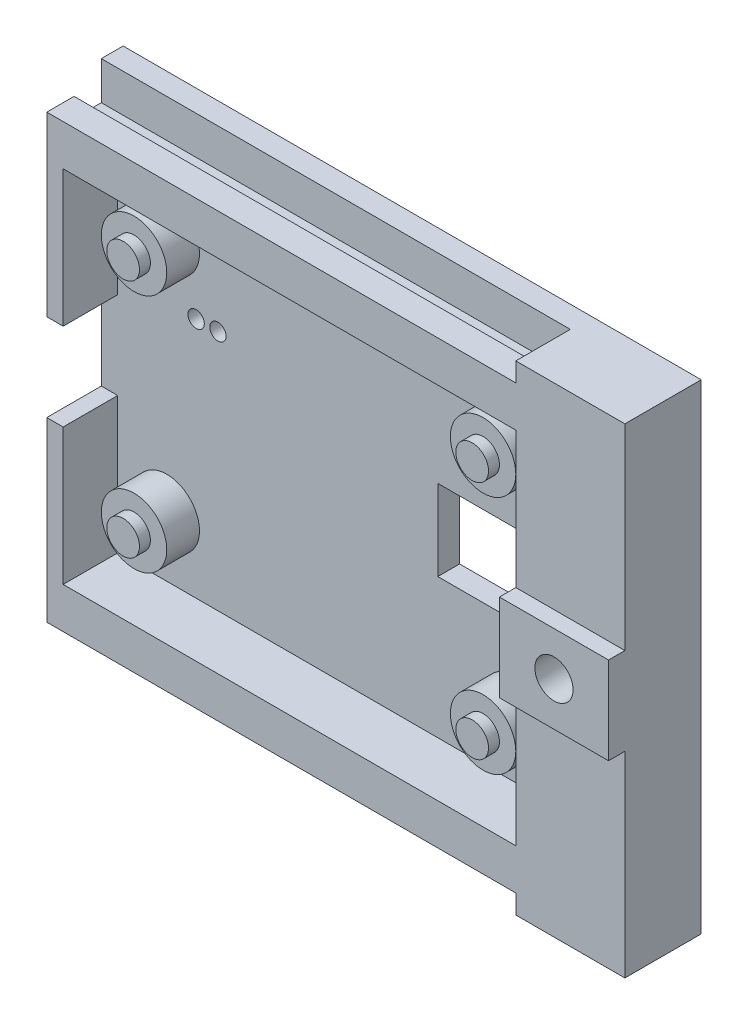
SolidWorks part; units mm, degrees
ref_plane "Alzado" through (0, 0, 0) normal (0, 0, 1) x (1, 0, 0)
ref_plane "Planta" through (0, 0, 0) normal (0, 1, 0) x (1, 0, 0)
ref_plane "Vista lateral" through (0, 0, 0) normal (1, 0, 0) x (0, 0, -1)
sketch "Croquis1" plane through (0, 0, 0) normal (0, 0, 1) x (1, 0, 0)
  line L0 (-22, 22) -> (-22, -22)
  line L1 (-22, -22) -> (31, -22)
  line L2 (31, -22) -> (31, 22)
  line L3 (31, 22) -> (-22, 22)
  line L7 (8.85, 3.7) -> (16.25, 3.7)
  line L8 (8.85, 3.7) -> (8.85, -3.7)
  line L9 (8.85, -3.7) -> (16.25, -3.7)
  line L10 (16.25, 3.7) -> (16.25, -3.7)
  line L11 (8.85, 3.7) -> (16.25, -3.7) construction
  line L12 (8.85, -3.7) -> (16.25, 3.7) construction
  line L13 (-20, 15) -> (20, 15) construction
  line L14 (-20, 15) -> (-20, -15) construction
  line L15 (-20, -15) -> (20, -15) construction
  line L16 (20, 15) -> (20, -15) construction
  line L17 (-20, 15) -> (20, -15) construction
  line L18 (-20, -15) -> (20, 15) construction
  circle A0 centre (-13.3084, 5.6686) radius 0.75
  circle A1 centre (-11.3084, 5.6686) radius 0.75
  point P0 (0, 0)
  point P3 (-22, 0)
  point P6 (12.55, 0)
  point P8 (0, 0)
  point P17 (8.85, 0)
  point P18 (16.25, 0)
  point P23 (0, 0)
  point P26 (-19.4293, -15)
  dimension "D4" = 7.4
  dimension "D9" = 2
  dimension "D10" = 1.5
  dimension "D1" = 44
  dimension "D2" = 2
  dimension "D3" = 7.4
  dimension "D5" = 7.45
  dimension "D6" = 40
  dimension "D7" = 30
  dimension "D8" = 11
  dimension "D11" = 6.6916
  dimension "D12" = 20.6686
extrude "Saliente-Extruir1" add sketch "Croquis1" along normal blind 2
sketch "Croquis4" plane through (0, 0, 2) normal (0, 0, 1) x (1, 0, 0)
  line L1 (-20, 15) -> (20, 15) construction
  line L2 (-20, 15) -> (-20, -15) construction
  line L3 (-20, -15) -> (20, -15) construction
  line L4 (20, 15) -> (20, -15) construction
  line L5 (-20, 15) -> (20, -15) construction
  line L6 (-20, -15) -> (20, 15) construction
  circle A0 centre (-16, -11) radius 1.5
  circle A1 centre (16, -11) radius 1.5
  circle A2 centre (16, 11) radius 1.5
  circle A3 centre (-16, 11) radius 1.5
  point P12 (0, 0)
  dimension "D1" = 3
  dimension "D2" = 30
  dimension "D3" = 40
  dimension "D4" = 4
  dimension "D5" = 4
  dimension "D6" = 4
  dimension "D7" = 4
extrude "Saliente-Extruir3" add sketch "Croquis4" along normal blind 4
sketch "Croquis5" plane through (0, 0, 0) normal (0, 0, -1) x (-1, 0, 0)
  line L0 (-31, -22) -> (-31, 22) construction
  circle A0 centre (-26, 0) radius 1.75
  dimension "D2" = 3.5
  dimension "D1" = 5
extrude "Cortar-Extruir1" cut sketch "Croquis5" against normal up to next
sketch "Croquis6" plane through (0, 0, 2) normal (0, 0, 1) x (1, 0, 0)
  line L0 (-22, -18.5) -> (21, -18.5)
  line L1 (-22, 22) -> (-22, -22) construction
  line L3 (-22, -18.5) -> (-22, 18.5)
  line L4 (-20.5, -16.5) -> (21, -16.5)
  line L7 (-20.5, 16.5) -> (21, 16.5)
  line L8 (-20.5, -16.5) -> (-20.5, 16.5)
  line L9 (21, 18.5) -> (-22, 18.5)
  line L11 (21, -18.5) -> (21, -22)
  line L12 (-22, -22) -> (31, -22) construction
  line L13 (21, -22) -> (31, -22)
  line L14 (31, -22) -> (31, 22)
  line L15 (31, 22) -> (21, 22)
  line L16 (31, 22) -> (-22, 22) construction
  line L17 (21, 22) -> (21, 18.5)
  line L18 (21, -16.5) -> (21, 16.5)
  circle A0 centre (26, 0) radius 1.75 construction
  circle A1 centre (26, 0) radius 1.75
  dimension "D1" = 37
  dimension "D2" = 2
  dimension "D3" = 2
  dimension "D4" = 18.5
  dimension "D5" = 43
  dimension "D6" = 1.5
extrude "Saliente-Extruir4" add sketch "Croquis6" along normal blind 5
sketch "Croquis7" plane through (0, 0, 7) normal (0, 0, 1) x (1, 0, 0)
  line L0 (-22, 18.5) -> (-22, 20.25)
  line L1 (-22, 22) -> (-22, 18.5) construction
  line L2 (-22, 20.25) -> (21, 20.25)
  line L3 (21, 22) -> (21, 18.5) construction
  line L4 (21, 20.25) -> (21, 18.5)
  line L5 (21, 18.5) -> (-22, 18.5)
  line L6 (-22, -18.5) -> (-22, -20.25)
  line L7 (-22, -18.5) -> (-22, -22) construction
  line L8 (-22, -20.25) -> (21, -20.25)
  line L9 (21, -18.5) -> (21, -22) construction
  line L10 (21, -20.25) -> (21, -18.5)
  line L11 (21, -18.5) -> (-22, -18.5)
extrude "Saliente-Extruir5" add sketch "Croquis7" against normal blind 2.5
sketch "Croquis8" plane through (0, 0, 7) normal (0, 0, 1) x (1, 0, 0)
  line L0 (-20.5, -4) -> (-20.5, 4)
  line L1 (-20.5, 16.5) -> (-20.5, -16.5) construction
  line L2 (-20.5, 4) -> (-22, 4)
  line L3 (-22, 20.25) -> (-22, -20.25) construction
  line L4 (-22, 4) -> (-22, -4)
  line L5 (-22, -4) -> (-20.5, -4)
  point P4 (-20.5, 0)
  dimension "D1" = 8
extrude "Cortar-Extruir3" cut sketch "Croquis8" against normal blind 5
sketch "Croquis9" plane through (0, 0, 0) normal (0, 0, -1) x (-1, 0, 0)
  circle A0 centre (-26, 0) radius 3.5
  dimension "D1" = 7
extrude "Cortar-Extruir4" cut sketch "Croquis9" against normal blind 5
sketch "Croquis10" plane through (0, 0, 2) normal (0, 0, 1) x (1, 0, 0)
  circle A0 centre (-16, 11) radius 3
  circle A1 centre (16, 11) radius 3
  circle A2 centre (16, -11) radius 3
  circle A3 centre (-16, -11) radius 3
  dimension "D1" = 6
extrude "Saliente-Extruir6" add sketch "Croquis10" along normal blind 3
sketch "Croquis12" plane through (0, 0, 7) normal (0, 0, 1) x (1, 0, 0)
  line L0 (21, -4) -> (21, 4)
  line L1 (21, -16.5) -> (21, 16.5) construction
  line L2 (21, -4) -> (31, -4)
  line L3 (31, -22) -> (31, 22) construction
  line L4 (31, -4) -> (31, 4)
  line L5 (31, 4) -> (21, 4)
  circle A0 centre (26, 0) radius 1.75 construction
  circle A1 centre (26, 0) radius 1.75
  point P4 (21, 0)
  dimension "D1" = 8
extrude "Saliente-Extruir7" add sketch "Croquis12" along normal blind 1.5
